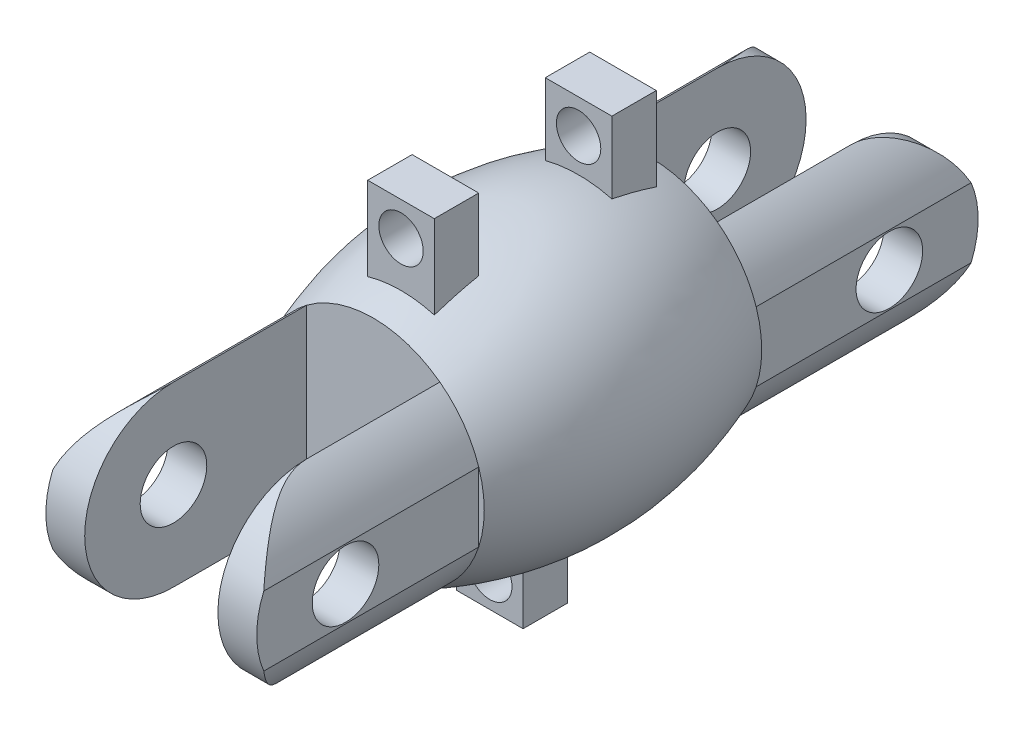
SolidWorks part; units mm, degrees
ref_plane "Front Plane" through (0, 0, 0) normal (0, 0, 1) x (1, 0, 0)
ref_plane "Top Plane" through (0, 0, 0) normal (0, 1, 0) x (1, 0, 0)
ref_plane "Right Plane" through (0, 0, 0) normal (1, 0, 0) x (0, 0, -1)
sketch "Sketch2" plane through (0, 0, 0) normal (1, 0, 0) x (0, 0, -1)
  line L0 (-12.5, 0) -> (12.5, 0)
  line L1 (-12.5, 0) -> (-12.5, 10)
  line L2 (12.5, 0) -> (12.5, 10)
  spline S0 degree 2 poles (-12.5, 10) (0, 15) (12.5, 10) knots 0 0 0 1 1 1
  point P3 (0, 0)
  dimension "D1" = 25
  dimension "D2" = 10
  dimension "D3" = 10
  dimension "D4" = 12.5
revolve "Revolve1" add sketch "Sketch2" angle 360 about L0
sketch "Sketch3" plane through (0, 0, 12.5) normal (0, 0, 1) x (1, 0, 0)
  line L1 (-9.5, 10) -> (9.5, 10)
  line L2 (-9.5, 10) -> (-9.5, -10)
  line L3 (-9.5, -10) -> (9.5, -10)
  line L4 (9.5, 10) -> (9.5, -10)
  line L5 (-9.5, 10) -> (9.5, -10) construction
  line L6 (-9.5, -10) -> (9.5, 10) construction
  point P0 (0, 0)
  dimension "D1" = 20
  dimension "D2" = 19
extrude "Boss-Extrude2" add sketch "Sketch3" along normal blind 20
sketch "Sketch4" plane through (0, 0, -12.5) normal (0, 0, -1) x (-1, 0, 0)
  line L1 (-9.5, 10) -> (9.5, 10)
  line L2 (-9.5, 10) -> (-9.5, -10)
  line L3 (-9.5, -10) -> (9.5, -10)
  line L4 (9.5, 10) -> (9.5, -10)
  line L5 (-9.5, 10) -> (9.5, -10) construction
  line L6 (-9.5, -10) -> (9.5, 10) construction
  point P0 (0, 0)
  dimension "D1" = 19
  dimension "D2" = 20
extrude "Boss-Extrude3" add sketch "Sketch4" along normal blind 20
sketch "Sketch5" plane through (0, 0, -12.5) normal (0, 0, -1) x (-1, 0, 0)
  circle A0 centre (0, 0) radius 10
  circle A1 centre (0, 0) radius 15
  arc A2 (9.5, -3.1225) -> (9.5, 3.1225) centre (0, 0) ccw construction
  dimension "D1" = 30
extrude "Cut-Extrude1" cut sketch "Sketch5" along normal through all
sketch "Sketch6" plane through (0, 0, 12.5) normal (0, 0, 1) x (1, 0, 0)
  circle A0 centre (0, 0) radius 10
  circle A1 centre (0, 0) radius 15
  arc A2 (9.5, -3.1225) -> (9.5, 3.1225) centre (0, 0) ccw construction
  dimension "D1" = 30
extrude "Cut-Extrude2" cut sketch "Sketch6" along normal through all
sketch "Sketch7" plane through (0, 0, 0) normal (0, 1, 0) x (1, 0, 0)
  line L0 (9.5, 32.5) -> (-9.5, 32.5) construction
  line L1 (-6, 32.5) -> (6, 32.5)
  line L2 (-6, 32.5) -> (-6, 12.5)
  line L3 (-6, 12.5) -> (6, 12.5)
  line L4 (6, 32.5) -> (6, 12.5)
  line L5 (9.5, 12.5) -> (-9.5, 12.5) construction
  line L6 (9.5, -12.5) -> (-9.5, -12.5) construction
  line L7 (-6, -12.5) -> (6, -12.5)
  line L8 (-6, -12.5) -> (-6, -32.5)
  line L9 (-6, -32.5) -> (6, -32.5)
  line L10 (6, -12.5) -> (6, -32.5)
  line L11 (-9.5, -32.5) -> (9.5, -32.5) construction
  line L12 (9.5, 32.5) -> (9.5, 12.5) construction
  dimension "D1" = 12
  dimension "D2" = 3.5
extrude "Cut-Extrude3" cut sketch "Sketch7" against normal through all both and the other way through all
sketch "Sketch8" plane through (-6, 0, 0) normal (1, 0, 0) x (0, 0, -1)
  line L0 (-12.5, -8) -> (-32.5, -8) construction
  line L1 (-32.5, 8) -> (-12.5, 8) construction
  line L2 (-32.5, -8) -> (-32.5, 8) construction
  line L3 (-24.5, -8) -> (-32.5, -8)
  line L4 (-32.5, -8) -> (-32.5, 8)
  line L5 (-32.5, 8) -> (-24.5, 8)
  arc A0 (-24.5, -8) -> (-24.5, 8) centre (-24.5, 0) cw
  line M1 (-32.5, 8) -> (-32.5, -8)
  line M2 (-32.5, -8) -> (-12.5, -8)
  line M4 (-12.5, 8) -> (-32.5, 8)
extrude "Cut-Extrude4" cut sketch "Sketch8" against normal through all both and the other way through all contours A0 M1 M4 | A0 L4 M2
sketch "Sketch9" plane through (-6, 0, 0) normal (1, 0, 0) x (0, 0, -1)
  line L0 (12.5, 8) -> (32.5, 8) construction
  line L1 (32.5, -8) -> (12.5, -8) construction
  line L2 (32.5, -8) -> (32.5, 8) construction
  line L3 (24.5, -8) -> (32.5, -8)
  line L4 (32.5, -8) -> (32.5, 8)
  line L5 (32.5, 8) -> (24.5, 8)
  arc A0 (24.5, 8) -> (24.5, -8) centre (24.5, 0) cw
  line M1 (32.5, -8) -> (32.5, 8)
  line M2 (32.5, 8) -> (12.5, 8)
  line M4 (12.5, -8) -> (32.5, -8)
extrude "Cut-Extrude5" cut sketch "Sketch9" against normal through all both and the other way through all contours A0 L4 M2 | A0 M1 M4
sketch "Sketch10" plane through (9.5, 0, 0) normal (1, 0, 0) x (0, 0, -1)
  line L0 (24.5, -3.1225) -> (24.5, 3.1225) construction
  line L1 (12.5, -3.1225) -> (31.8655, -3.1225) construction
  line L2 (31.8655, 3.1225) -> (12.5, 3.1225) construction
  line L3 (-24.5, -3.1225) -> (-24.5, 3.1225) construction
  line L4 (-31.8655, -3.1225) -> (-12.5, -3.1225) construction
  line L5 (-12.5, 3.1225) -> (-31.8655, 3.1225) construction
  circle A0 centre (24.5, 0) radius 3
  circle A1 centre (-24.5, 0) radius 3
  arc A4 (-31.8655, 3.1225) -> (-31.8655, -3.1225) centre (-24.5, 0) ccw construction
  arc A5 (31.8655, -3.1225) -> (31.8655, 3.1225) centre (24.5, 0) ccw construction
  point P10 (24.5, 0)
  point P17 (-24.5, 0)
  dimension "D1" = 6
  dimension "D2" = 6
extrude "Cut-Extrude8" cut sketch "Sketch10" against normal through all both and the other way through all
sketch "Sketch11" plane through (0, 0, 0) normal (0, 1, 0) x (1, 0, 0)
  line L1 (3, -2) -> (-3, -2)
  line L2 (3, -2) -> (3, 2)
  line L3 (3, 2) -> (-3, 2)
  line L4 (-3, -2) -> (-3, 2)
  line L5 (3, -2) -> (-3, 2) construction
  line L6 (3, 2) -> (-3, -2) construction
  point P0 (0, 0)
  dimension "D1" = 4
  dimension "D2" = 6
extrude "Boss-Extrude5" add sketch "Sketch11" against normal blind 18 contours L3 L4 L1 L2
sketch "Sketch12" plane through (0, 0, -2) normal (0, 0, -1) x (-1, 0, 0)
  line L0 (0, -12.436) -> (0, -18) construction
  line L1 (-3, -18) -> (3, -18) construction
  circle A0 centre (0, -15.218) radius 2
  arc A1 (-3, -12.0687) -> (3, -12.0687) centre (0, 0) ccw construction
  dimension "D1" = 4
extrude "Cut-Extrude9" cut sketch "Sketch12" against normal through all
sketch "Sketch13" plane through (0, 0, 0) normal (0, 1, 0) x (1, 0, 0)
  line L1 (-3, 10) -> (3, 10)
  line L2 (-3, 10) -> (-3, 6)
  line L3 (-3, 6) -> (3, 6)
  line L4 (3, 10) -> (3, 6)
  line L5 (-3, 10) -> (3, 6) construction
  line L6 (-3, 6) -> (3, 10) construction
  line L7 (-3, -6) -> (3, -6)
  line L8 (-3, -6) -> (-3, -10)
  line L9 (-3, -10) -> (3, -10)
  line L10 (3, -6) -> (3, -10)
  line L11 (-3, -6) -> (3, -10) construction
  line L12 (-3, -10) -> (3, -6) construction
  point P0 (0, 8)
  point P5 (0, -8)
  dimension "D1" = 6
  dimension "D2" = 4
  dimension "D3" = 4
  dimension "D4" = 6
  dimension "D5" = 6
  dimension "D6" = 6
extrude "Boss-Extrude6" add sketch "Sketch13" along normal blind 18
sketch "Sketch14" plane through (0, 0, -6) normal (0, 0, 1) x (1, 0, 0)
  line L0 (0, 18) -> (0, 11.924) construction
  line L1 (-3, 18) -> (3, 18) construction
  circle A0 centre (0, 14.962) radius 2
  arc A1 (3, 11.5404) -> (-3, 11.5404) centre (0, 0) ccw construction
  dimension "D1" = 4
extrude "Cut-Extrude10" cut sketch "Sketch14" against normal through all both and the other way through all
scale "Scale1" scale about centroid uniform scaling yes scale factor 0.75
